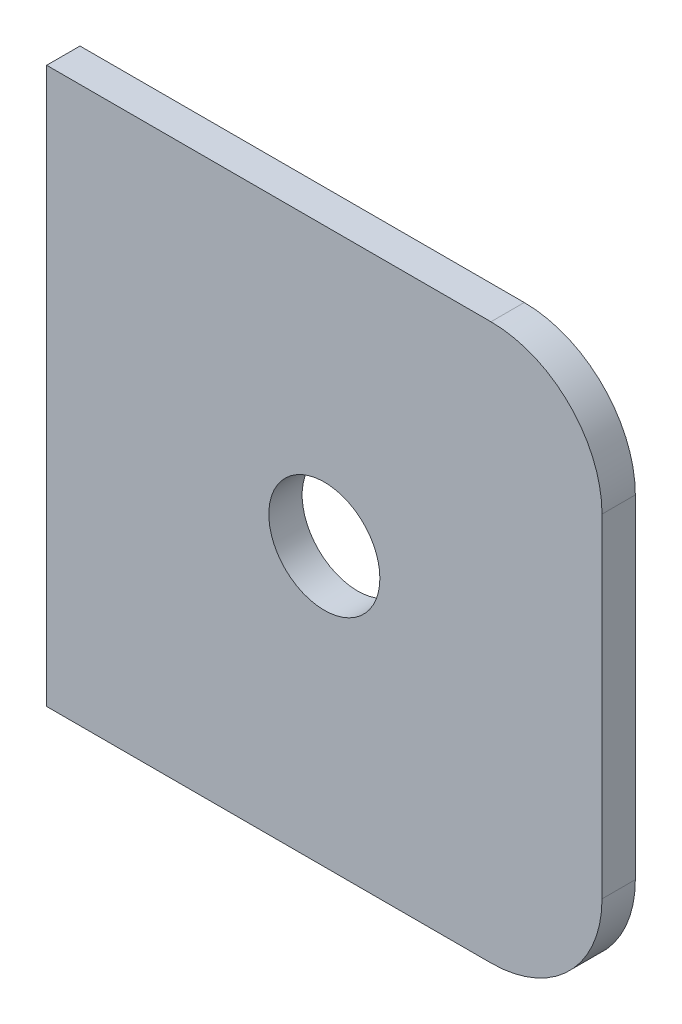
SolidWorks part; units mm, degrees
ref_plane "Front Plane" through (0, 0, 0) normal (0, 0, 1) x (1, 0, 0)
ref_plane "Top Plane" through (0, 0, 0) normal (0, 1, 0) x (1, 0, 0)
ref_plane "Right Plane" through (0, 0, 0) normal (1, 0, 0) x (0, 0, -1)
sketch "Sketch1" plane through (0, 0, 0) normal (0, 0, 1) x (1, 0, 0)
  line L1 (-24.0116, 26.3081) -> (15.9884, 26.3081)
  line L2 (-24.0116, 26.3081) -> (-24.0116, -23.6919)
  line L3 (-24.0116, -23.6919) -> (15.9884, -23.6919)
  line L4 (25.9884, 16.3081) -> (25.9884, -13.6919)
  circle A0 centre (0.9884, 1.3081) radius 5
  arc A1 (25.9884, 16.3081) -> (15.9884, 26.3081) centre (15.9884, 16.3081) ccw
  arc A2 (15.9884, -23.6919) -> (25.9884, -13.6919) centre (15.9884, -13.6919) ccw
  point P17 (25.9884, 26.3081)
  dimension "D3" = 25
  dimension "D5" = 10
  dimension "D6" = 10
  dimension "D1" = 50
  dimension "D2" = 50
  dimension "D4" = 25
extrude "Boss-Extrude1" add sketch "Sketch1" along normal blind 3
